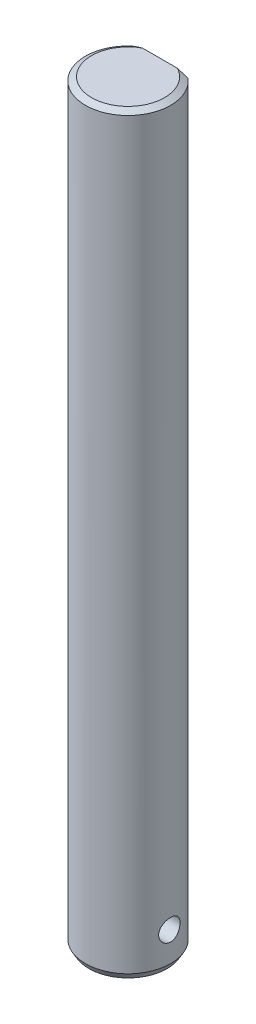
SolidWorks part; units mm, degrees
ref_plane "Front Plane" through (0, 0, 0) normal (0, 0, 1) x (1, 0, 0)
ref_plane "Top Plane" through (0, 0, 0) normal (0, 1, 0) x (1, 0, 0)
ref_plane "Right Plane" through (0, 0, 0) normal (1, 0, 0) x (0, 0, -1)
sketch "Sketch1" plane through (0, 0, 0) normal (0, 1, 0) x (1, 0, 0)
  circle A0 centre (0, 0) radius 6
  dimension "D1" = 12
extrude "Boss-Extrude1" add sketch "Sketch1" along normal blind 106
sketch "Sketch2" plane through (0, 106, 0) normal (0, 1, 0) x (1, 0, 0)
  line L1 (-9.5625, 11.3009) -> (9.8923, 11.3009)
  line L2 (-9.5625, 11.3009) -> (-9.5625, 4.5)
  line L3 (-9.5625, 4.5) -> (9.8923, 4.5)
  line L4 (9.8923, 11.3009) -> (9.8923, 4.5)
  dimension "D1" = 4.5
extrude "Cut-Extrude1" cut sketch "Sketch2" against normal blind 10
sketch "Sketch3" plane through (0, 0, 0) normal (1, 0, 0) x (0, 0, -1)
  circle A0 centre (0, 5) radius 1.5
  dimension "D1" = 3
  dimension "D2" = 5
extrude "Cut-Extrude2" cut sketch "Sketch3" against normal mid plane 40
chamfer "Chamfer1" distance 0.5 angle 60 2 edges at (0, 106, 6) (0, 0, 6)
